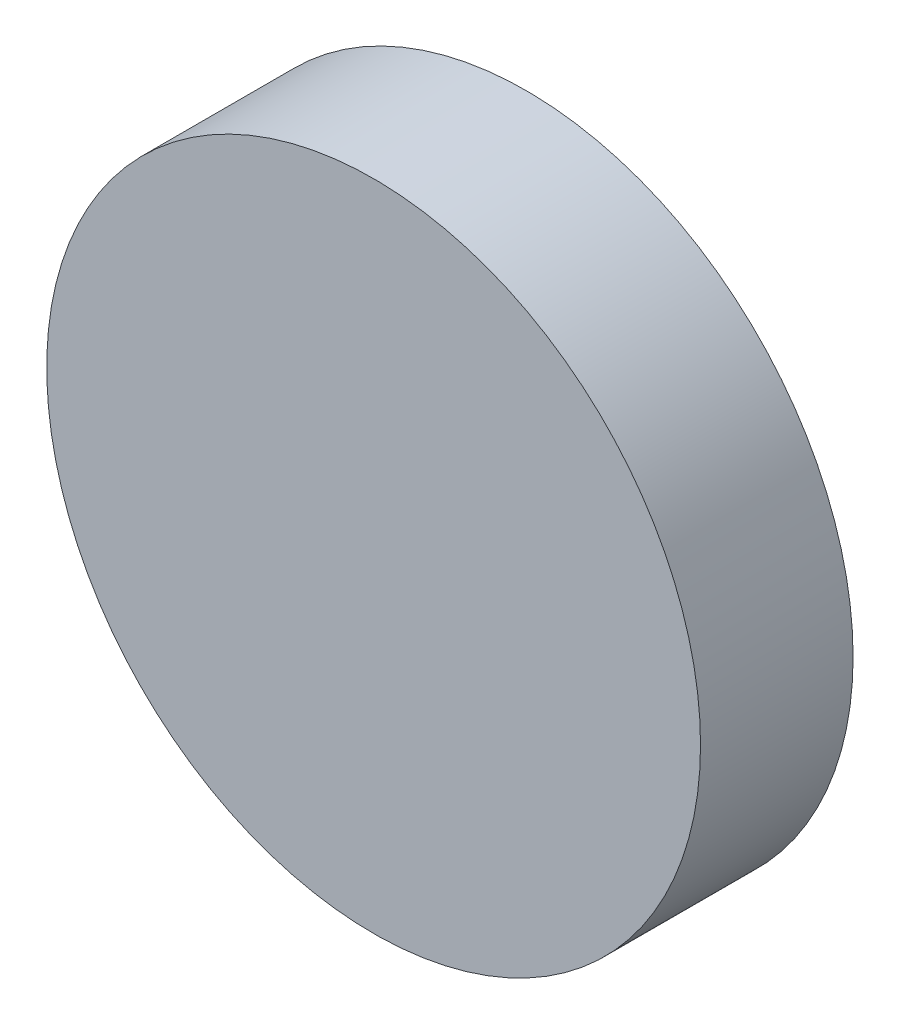
SolidWorks part; units mm, degrees
ref_plane "前视基准面" through (0, 0, 0) normal (0, 0, 1) x (1, 0, 0)
ref_plane "上视基准面" through (0, 0, 0) normal (0, 1, 0) x (1, 0, 0)
ref_plane "右视基准面" through (0, 0, 0) normal (1, 0, 0) x (0, 0, -1)
sketch "草图1" plane through (0, 0, 0) normal (0, 0, 1) x (1, 0, 0)
  circle A0 centre (0, 0) radius 5
  circle A1 centre (0, 0) radius 7.5
  dimension "D1" = 10
  dimension "D2" = 15
extrude "凸台-拉伸1" add sketch "草图1" along normal blind 2
sketch "草图2" plane through (0, 0, 2) normal (0, 0, 1) x (1, 0, 0)
  circle A1 centre (0, 0) radius 7.5
  circle A2 centre (0, 0) radius 7.5
  dimension "D1" = 0
extrude "凸台-拉伸2" add sketch "草图2" along normal blind 1.5
